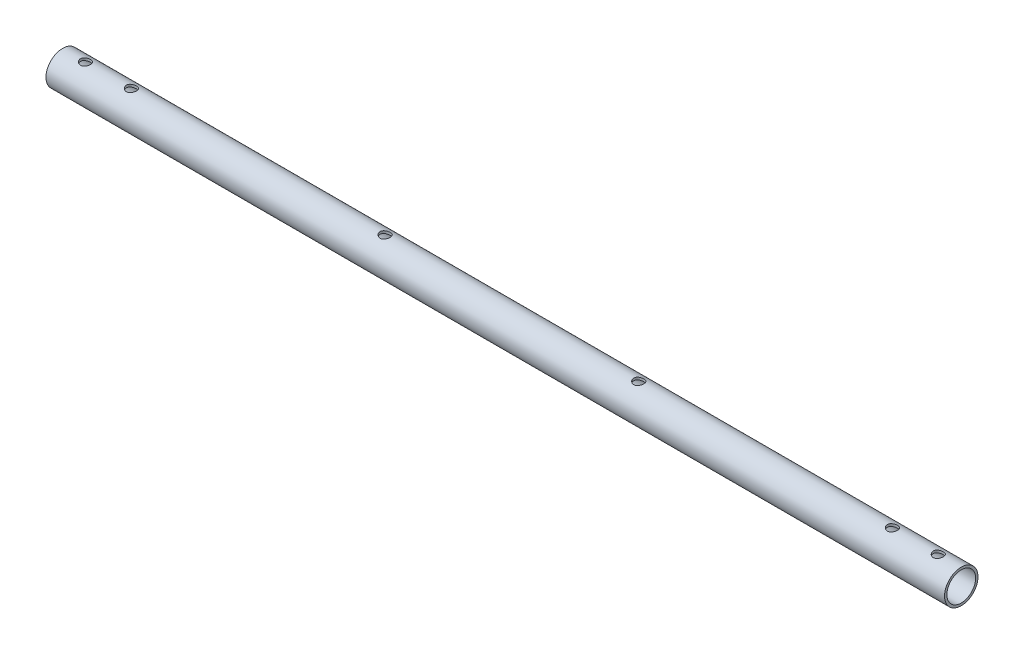
SolidWorks part; units mm, degrees
material "ASTM A36 Steel"
ref_plane "Front Plane" through (0, 0, 0) normal (0, 0, 1) x (1, 0, 0)
ref_plane "Top Plane" through (0, 0, 0) normal (0, 1, 0) x (1, 0, 0)
ref_plane "Right Plane" through (0, 0, 0) normal (1, 0, 0) x (0, 0, -1)
sketch "Sketch1" plane through (0, 0, 0) normal (1, 0, 0) x (0, 0, -1)
  circle A0 centre (0, 0) radius 36.5
  circle A1 centre (0, 0) radius 31.34
  dimension "D1" = 73
  dimension "D2" = 5.16
extrude "Boss-Extrude1" add sketch "Sketch1" along normal blind 1960
sketch "Sketch2" plane through (0, 0, 0) normal (0, 1, 0) x (1, 0, 0)
  line L0 (0, 36.5) -> (0, -36.5) construction
  circle A0 centre (50, 0) radius 11
  dimension "D1" = 22
  dimension "D2" = 50
extrude "Cut-Extrude1" cut sketch "Sketch2" against normal through all both and the other way through all
sketch "Sketch3" plane through (0, 0, 0) normal (0, 1, 0) x (1, 0, 0)
  circle A0 centre (150, 0) radius 11
  circle A1 centre (50, 0) radius 11 construction
  dimension "D1" = 22
  dimension "D2" = 100
extrude "Cut-Extrude2" cut sketch "Sketch3" against normal through all both and the other way through all
pattern_linear "LPattern1" count 4 spacing 553.33 along (1, 0, 0) of "Cut-Extrude2"
sketch "Sketch4" plane through (0, 0, 0) normal (0, 1, 0) x (1, 0, 0)
  circle A0 centre (1909.99, 0) radius 11
  circle A1 centre (1809.99, 0) radius 11 construction
  dimension "D1" = 22
  dimension "D2" = 100
extrude "Cut-Extrude3" cut sketch "Sketch4" against normal through all both and the other way through all
